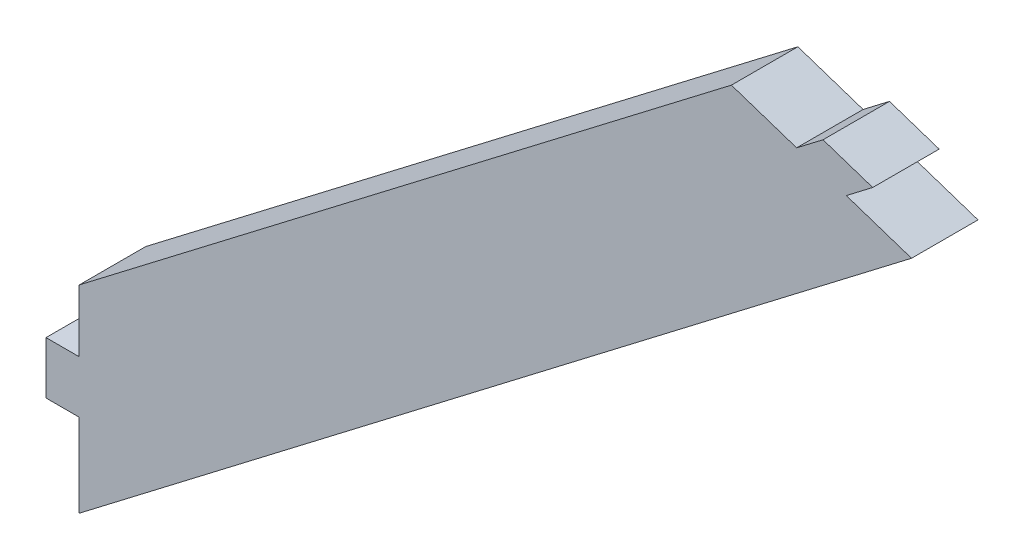
SolidWorks part; units mm, degrees
material "6061 Alloy"
ref_plane "Front Plane" through (0, 0, 0) normal (0, 0, 1) x (1, 0, 0)
ref_plane "Top Plane" through (0, 0, 0) normal (0, 1, 0) x (1, 0, 0)
ref_plane "Right Plane" through (0, 0, 0) normal (1, 0, 0) x (0, 0, -1)
sketch "Sketch1" plane through (0, 0, 0) normal (0, 0, 1) x (1, 0, 0)
  line L1 (-29.2012, -67.0333) -> (50.3028, -6.1889)
  line L2 (1.4346, -24.6992) -> (-29.2012, -48.1447)
  line L3 (1.4346, -24.6992) -> (33.0966, -0.4683)
  line L4 (33.0966, -0.4683) -> (39.3274, -2.5399)
  line L12 (44.072, -4.1174) -> (46.5934, -2.1878)
  line L13 (39.3274, -2.5399) -> (41.8488, -0.6103)
  line L14 (41.8488, -0.6103) -> (46.5934, -2.1878)
  line L19 (-29.2012, -54.089) -> (-32.3762, -54.089)
  line L20 (-32.3762, -54.089) -> (-32.3762, -59.089)
  line L21 (-32.3762, -59.089) -> (-29.2012, -59.089)
  line L22 (-29.2012, -48.1447) -> (-29.2012, -54.089)
  line L23 (-29.2012, -59.089) -> (-29.2012, -67.0333)
  line L24 (44.072, -4.1174) -> (50.3028, -6.1889)
extrude "Boss-Extrude1" add sketch "Sketch1" along normal blind 6.35 contours L2 L22 L19 L20 L21 L23 L1 L24 L12 L14 L13 L4 L3
sketch "Sketch4" plane through (0, 0, 0) normal (0, 0, 1) x (1, 0, 0)
  line L0 (50.3028, -6.1889) -> (-29.2012, -48.1447)
  line L1 (-29.2012, -29.2561) -> (33.0966, -0.4683)
  line L2 (33.0966, -0.4683) -> (39.3274, -2.5399)
  line L3 (39.3274, -2.5399) -> (41.8488, -0.6103)
  line L4 (41.8488, -0.6103) -> (46.5934, -2.1878)
  line L5 (46.5934, -2.1878) -> (44.072, -4.1174)
  line L6 (44.072, -4.1174) -> (46.5934, -2.1878) construction
  line L7 (44.072, -4.1174) -> (50.3028, -6.1889) construction
  line L8 (44.072, -4.1174) -> (50.3028, -6.1889)
  line L26 (-29.2012, -29.2561) -> (-29.2012, -35.2004)
  line L27 (-29.2012, -35.2004) -> (-32.3762, -35.2004)
  line L28 (-32.3762, -35.2004) -> (-32.3762, -40.2004)
  line L29 (-32.3762, -40.2004) -> (-29.2012, -40.2004)
  line L30 (-29.2012, -40.2004) -> (-29.2012, -48.1447)
sketch "Sketch3" [suppressed] plane through (0, 0, 6.35) normal (0, 0, 1) x (1, 0, 0)
  line L12 (33.0966, -0.4683) -> (-29.2012, -48.1447)
  line L13 (-29.2012, -48.1447) -> (-29.2012, -67.0333)
  line L18 (-29.2012, -67.0333) -> (50.3028, -6.1889)
  line L19 (50.3028, -6.1889) -> (33.0966, -0.4683)
  line L24 (33.0966, -0.4683) -> (-29.2012, -48.1447)
  line L25 (-29.2012, -48.1447) -> (-29.2012, -67.0333)
  line L30 (-29.2012, -67.0333) -> (50.3028, -6.1889)
  line L31 (50.3028, -6.1889) -> (33.0966, -0.4683)
  dimension "D1" = 0
